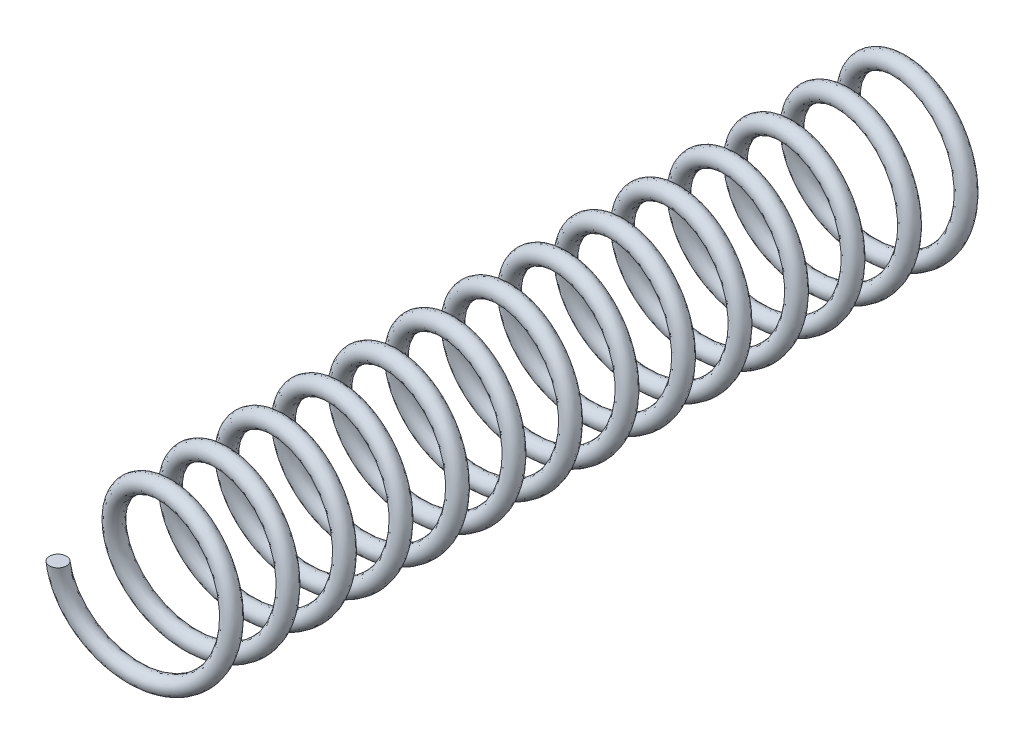
SolidWorks part; units mm, degrees
ref_plane "Plan de face" through (0, 0, 0) normal (0, 0, 1) x (1, 0, 0)
ref_plane "Plan de dessus" through (0, 0, 0) normal (0, 1, 0) x (1, 0, 0)
ref_plane "Plan de droite" through (0, 0, 0) normal (1, 0, 0) x (0, 0, -1)
sketch "Esquisse1" plane through (0, 0, 0) normal (0, 0, 1) x (1, 0, 0)
  circle A0 centre (0, 0) radius 15
  dimension "D1" = 30
curve "Hélice/Spirale1" pitch 10 height 140 turns 14
sketch "Esquisse2" plane through (0, 0, 0) normal (1, 0, 0) x (0, 0, -1)
  circle A0 centre (-140.3562, -12.8021) radius 1.5
  dimension "D1" = 3
sweep "Balayage1" add profiles "Esquisse2" path "Hélice/Spirale1"
